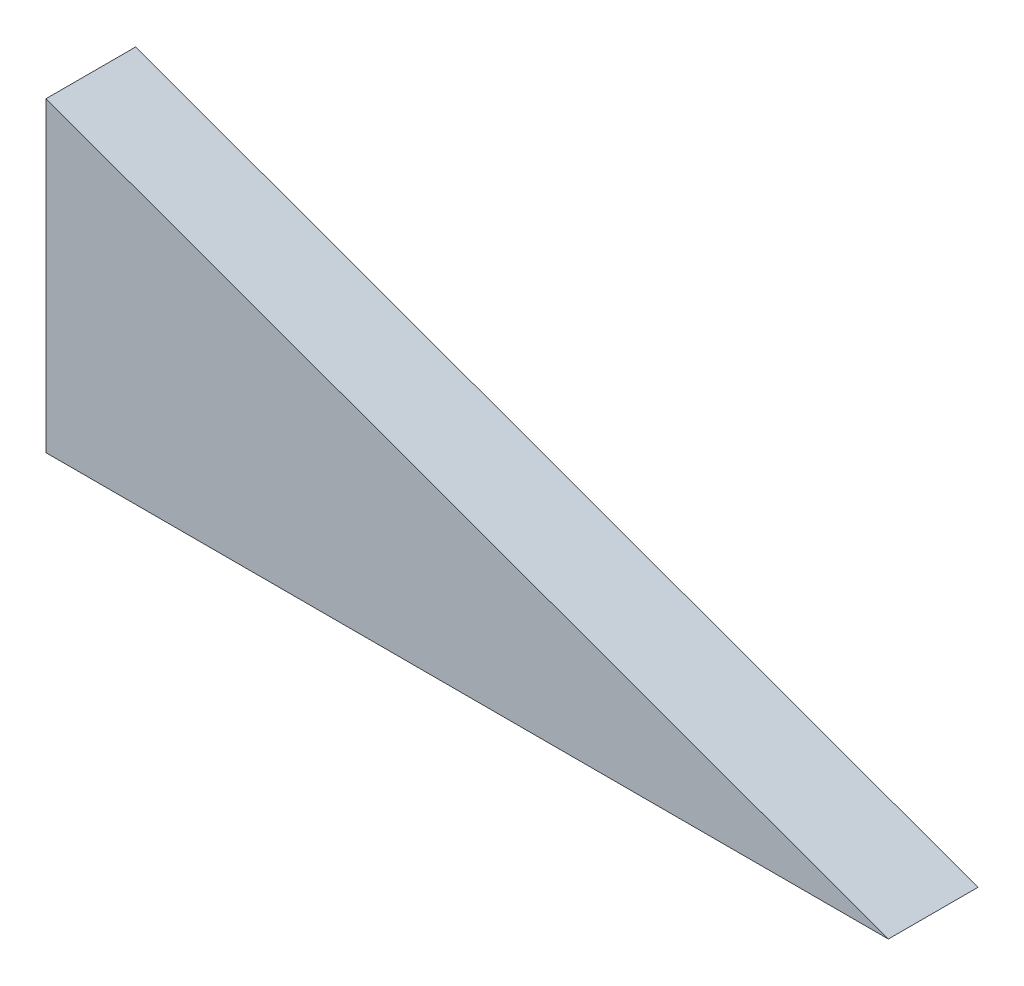
SolidWorks part; units mm, degrees
ref_plane "Plan de face" through (0, 0, 0) normal (0, 0, 1) x (1, 0, 0)
ref_plane "Plan de dessus" through (0, 0, 0) normal (0, 1, 0) x (1, 0, 0)
ref_plane "Plan de droite" through (0, 0, 0) normal (1, 0, 0) x (0, 0, -1)
sketch "Esquisse1" plane through (0, 0, 0) normal (0, 0, 1) x (1, 0, 0)
  line L0 (-101.3457, -21.0299) -> (-54.3611, -21.0299)
  line L1 (-54.3611, -21.0299) -> (-101.3457, -3.9289)
  line L2 (-101.3457, -3.9289) -> (-101.3457, -21.0299)
  dimension "D1" = 20
  dimension "D2" = 50
extrude "Boss.-Extru.1" add sketch "Esquisse1" along normal blind 5
